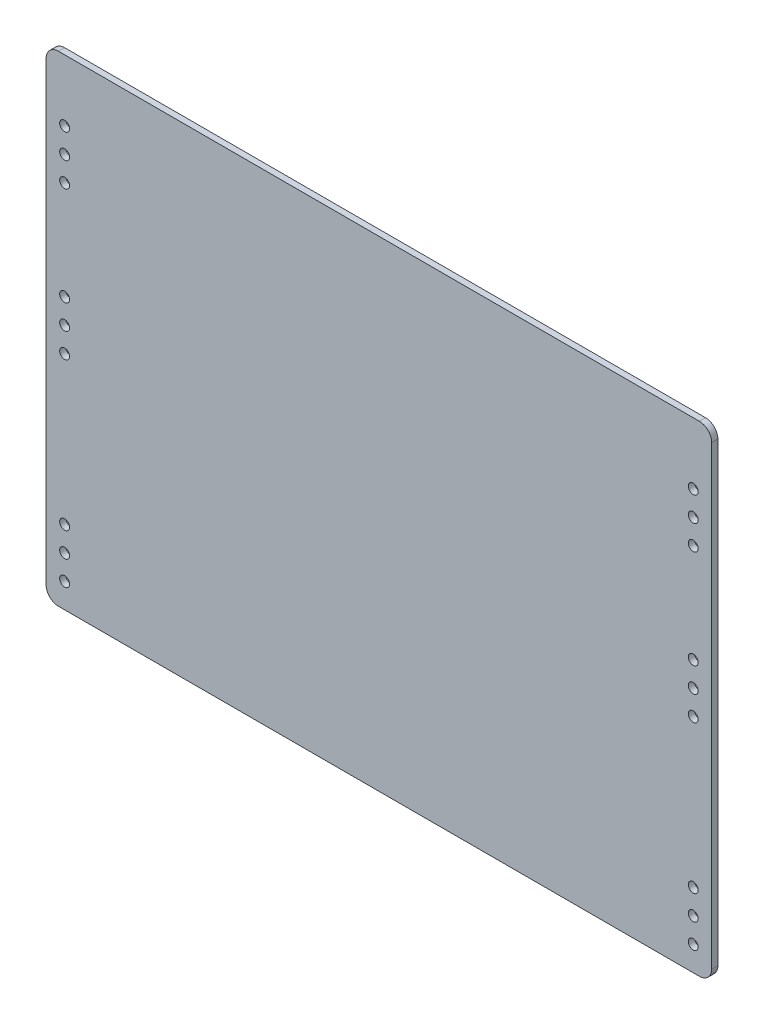
SolidWorks part; units mm, degrees
material "PC High Viscosity"
ref_plane "Front Plane" through (0, 0, 0) normal (0, 0, 1) x (1, 0, 0)
ref_plane "Top Plane" through (0, 0, 0) normal (0, 1, 0) x (1, 0, 0)
ref_plane "Right Plane" through (0, 0, 0) normal (1, 0, 0) x (0, 0, -1)
sketch "Sketch1" plane through (0, 0, 0) normal (0, 0, 1) x (1, 0, 0)
  line L0 (171.45, 0) -> (171.45, 247.65) construction
  line L1 (0, 0) -> (342.9, 0)
  line L2 (0, 0) -> (0, 247.65)
  line L3 (0, 247.65) -> (342.9, 247.65)
  line L4 (342.9, 0) -> (342.9, 247.65)
  line L5 (9.525, 247.65) -> (9.525, 0) construction
  line L6 (333.375, 247.65) -> (333.375, 0) construction
  circle A0 centre (9.525, 12.7) radius 2.5527
  circle A1 centre (9.525, 25.4) radius 2.5527
  circle A2 centre (9.525, 38.1) radius 2.5527
  circle A3 centre (9.525, 114.3) radius 2.5527
  circle A4 centre (9.525, 127) radius 2.5527
  circle A5 centre (9.525, 139.7) radius 2.5527
  circle A6 centre (9.525, 215.9) radius 2.5527
  circle A7 centre (9.525, 203.2) radius 2.5527
  circle A8 centre (9.525, 190.5) radius 2.5527
  circle A9 centre (333.375, 215.9) radius 2.5527
  circle A10 centre (333.375, 203.2) radius 2.5527
  circle A11 centre (333.375, 190.5) radius 2.5527
  circle A12 centre (333.375, 139.7) radius 2.5527
  circle A13 centre (333.375, 127) radius 2.5527
  circle A14 centre (333.375, 114.3) radius 2.5527
  circle A15 centre (333.375, 38.1) radius 2.5527
  circle A16 centre (333.375, 25.4) radius 2.5527
  circle A17 centre (333.375, 12.7) radius 2.5527
  dimension "D3" = 5.1054
  dimension "D1" = 342.9
  dimension "D2" = 12.7
  dimension "D4" = 12.7
  dimension "D5" = 12.7
  dimension "D6" = 12.7
  dimension "D7" = 12.7
  dimension "D8" = 12.7
  dimension "D9" = 12.7
  dimension "D10" = 50.8
  dimension "D11" = 76.2
  dimension "D12" = 31.75
  dimension "D13" = 323.85
extrude "Boss-Extrude1" add sketch "Sketch1" along normal blind 3.175
fillet "Fillet1" radius 6.35 4 edges at (0, 247.65, 1.5875) (342.9, 0, 1.5875) (0, 0, 1.5875) (342.9, 247.65, 1.5875)
